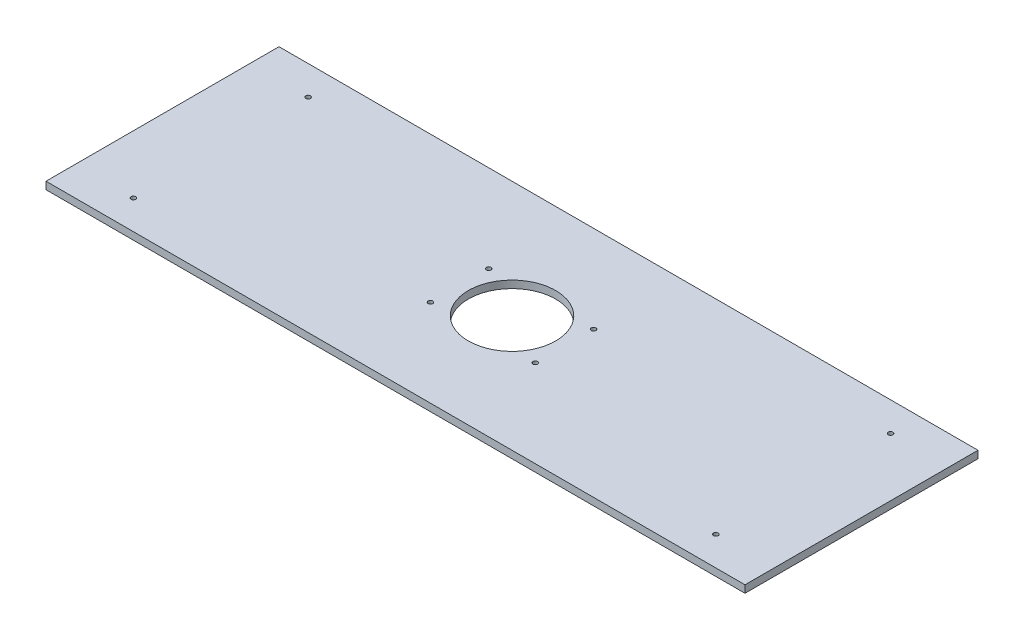
SolidWorks part; units mm, degrees
ref_plane "Front Plane" through (0, 0, 0) normal (0, 0, 1) x (1, 0, 0)
ref_plane "Top Plane" through (0, 0, 0) normal (0, 1, 0) x (1, 0, 0)
ref_plane "Right Plane" through (0, 0, 0) normal (1, 0, 0) x (0, 0, -1)
sketch "Sketch1" plane through (0, 0, 0) normal (0, 1, 0) x (1, 0, 0)
  line L0 (0, 400) -> (1200, 0) construction
  line L1 (0, 0) -> (1200, 0)
  line L2 (0, 0) -> (0, 400)
  line L3 (0, 400) -> (1200, 400)
  line L4 (1200, 0) -> (1200, 400)
  line L5 (100, 200) -> (1100, 200) construction
  line L6 (510, 150) -> (690, 150)
  line L7 (510, 150) -> (510, 250)
  line L8 (510, 250) -> (690, 250)
  line L9 (690, 150) -> (690, 250)
  line L10 (510, 150) -> (690, 250) construction
  line L11 (510, 250) -> (690, 150) construction
  line L12 (100, 350) -> (100, 50) construction
  line L13 (1100, 350) -> (1100, 50) construction
  circle A0 centre (510, 250) radius 4
  circle A1 centre (690, 250) radius 4
  circle A2 centre (510, 150) radius 4
  circle A3 centre (690, 150) radius 4
  circle A4 centre (600, 200) radius 75
  circle A5 centre (100, 350) radius 4
  circle A6 centre (100, 50) radius 4
  circle A7 centre (1100, 350) radius 4
  circle A8 centre (1100, 50) radius 4
  point P5 (600, 200)
  point P18 (600, 200)
  point P21 (100, 200)
  point P26 (1100, 200)
  dimension "D5" = 8
  dimension "D6" = 8
  dimension "D7" = 8
  dimension "D8" = 8
  dimension "D9" = 150
  dimension "D12" = 300
  dimension "D13" = 8
  dimension "D14" = 8
  dimension "D1" = 1200
  dimension "D2" = 400
  dimension "D3" = 180
  dimension "D4" = 100
  dimension "D10" = 1000
  dimension "D11" = 300
extrude "Boss-Extrude1" add sketch "Sketch1" along normal blind 12.7 contours L1 L4 L3 L2 A8 A7 A6 A5 A4 L8 A1 L9 A3 L6 A2 L7 A0 | A4 L8 A0 L7 A2 L6 | A4 L6 A3 L9 A1 L8
